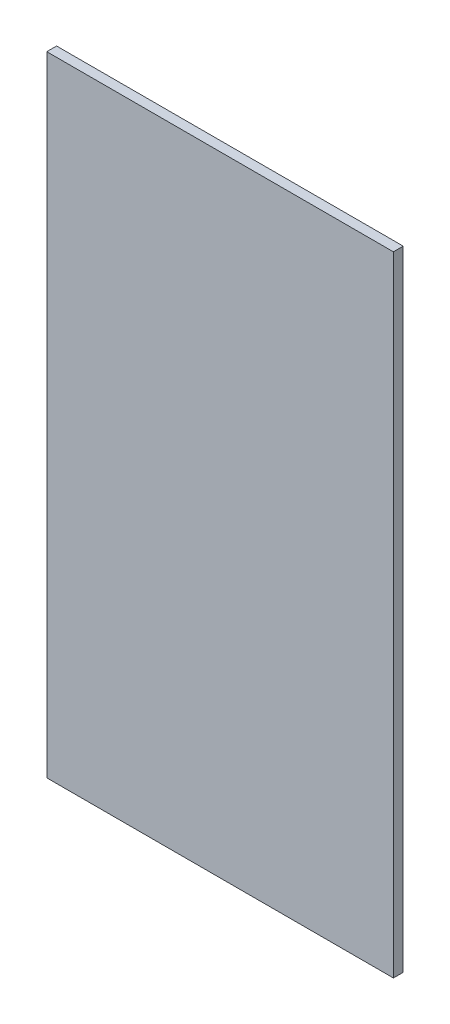
SolidWorks part; units mm, degrees
ref_plane "Front" through (0, 0, 0) normal (0, 0, 1) x (1, 0, 0)
ref_plane "Top" through (0, 0, 0) normal (0, 1, 0) x (1, 0, 0)
ref_plane "Right" through (0, 0, 0) normal (1, 0, 0) x (0, 0, -1)
sketch "Sketch1" plane through (0, 0, 0) normal (0, 0, 1) x (1, 0, 0)
  line L1 (-43.2328, -162.4203) -> (68.7672, -162.4203)
  line L2 (-43.2328, -162.4203) -> (-43.2328, 40.7797)
  line L3 (-43.2328, 40.7797) -> (68.7672, 40.7797)
  line L4 (68.7672, -162.4203) -> (68.7672, 40.7797)
  dimension "D1" = 112
  dimension "D2" = 203.2
extrude "Boss-Extrude1" add sketch "Sketch1" along normal blind 3.175
